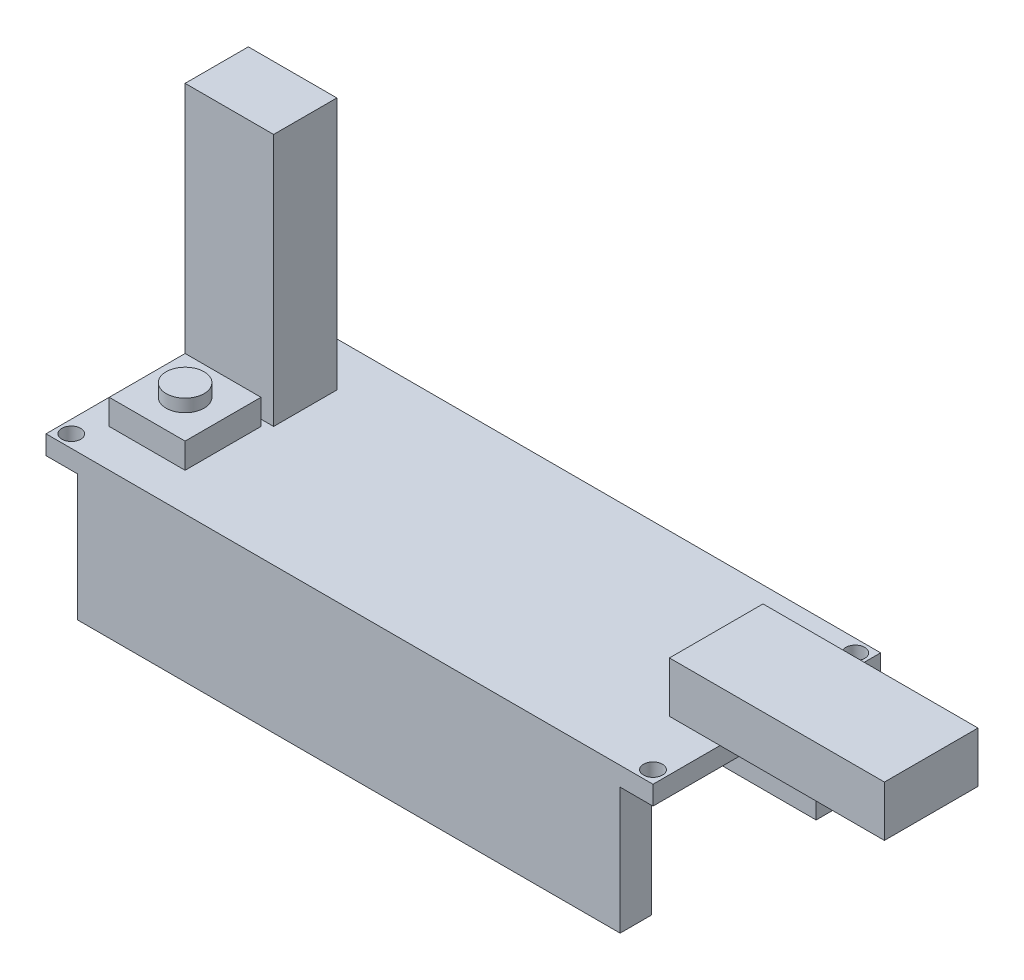
SolidWorks part; units mm, degrees
ref_plane "Спереди" through (0, 0, 0) normal (0, 0, 1) x (1, 0, 0)
ref_plane "Сверху" through (0, 0, 0) normal (0, 1, 0) x (1, 0, 0)
ref_plane "Справа" through (0, 0, 0) normal (1, 0, 0) x (0, 0, -1)
sketch "Эскиз1" plane through (0, 0, 0) normal (0, 1, 0) x (1, 0, 0)
  line L0 (0, 0) -> (-48, 0)
  line L1 (-48, 0) -> (-48, 18)
  line L2 (-48, 18) -> (0, 18)
  line L3 (0, 18) -> (0, 0)
extrude "Бобышка-Вытянуть1" add sketch "Эскиз1" along normal blind 1.5
sketch "Эскиз2" plane through (0, 1.5, 0) normal (0, 1, 0) x (1, 0, 0)
  line L0 (0, 9) -> (0, 12.7)
  line L1 (0, 0) -> (0, 18) construction
  line L2 (0, 12.7) -> (-4, 12.7)
  line L3 (-4, 12.7) -> (-4, 5.3)
  line L4 (-4, 5.3) -> (13, 5.3)
  line L5 (13, 5.3) -> (13, 12.7)
  line L6 (13, 12.7) -> (0, 12.7)
  line M1 (0, 0) -> (0, 18)
extrude "Бобышка-Вытянуть2" add sketch "Эскиз2" along normal blind 4 contours L5 L6 L4 M1 | L3 L4 L2 M1
sketch "Эскиз4" plane through (0, 0, 0) normal (0, -1, 0) x (-1, 0, 0)
  line L0 (0, 18) -> (2.6, 18)
  line L1 (0, 18) -> (48, 18) construction
  line L2 (48, 18) -> (45.5, 18)
  line L3 (45.5, 18) -> (2.6, 18)
  line L4 (2.6, 18) -> (2.6, 15.5)
  line L5 (2.6, 15.5) -> (45.5, 15.5)
  line L6 (45.5, 15.5) -> (45.5, 18)
  line L7 (0, 9) -> (48, 9) construction
  line L10 (45.5, 2.5) -> (45.5, 0)
  line L11 (2.6, 2.5) -> (45.5, 2.5)
  line L12 (2.6, 0) -> (2.6, 2.5)
  line L13 (45.5, 0) -> (2.6, 0)
  line L14 (48, 0) -> (45.5, 0)
  line L15 (0, 0) -> (2.6, 0)
  line M2 (0, 0) -> (48, 0)
  line M4 (48, 18) -> (0, 18)
extrude "Бобышка-Вытянуть3" add sketch "Эскиз4" along normal blind 10 contours L5 L6 L4 M4 | L12 L10 L11 M2
sketch "Эскиз5" plane through (0, 1.5, 0) normal (0, 1, 0) x (1, 0, 0)
  line L3 (-39.5, 18) -> (-39.5, 14.5)
  line L4 (0, 18) -> (-48, 18) construction
  line L5 (-39.5, 14.5) -> (-39.5, 9.5)
  line L6 (-39.5, 9.5) -> (-46.5, 9.5)
  line L7 (-46.5, 9.5) -> (-46.5, 14.5)
  line L8 (-46.5, 14.5) -> (-39.5, 14.5)
  dimension "D1" = 3.5
extrude "Бобышка-Вытянуть4" add sketch "Эскиз5" along normal blind 20 contours L8 L7 L6 L5
sketch "Эскиз6" plane through (0, 1.5, 0) normal (0, 1, 0) x (1, 0, 0)
  line L0 (-48, 0) -> (-46, 0)
  line L1 (-48, 0) -> (0, 0) construction
  line L2 (-46, 0) -> (-46, 3)
  line L3 (-46, 3) -> (-46, 9)
  line L4 (-46, 9) -> (-40, 9)
  line L5 (-40, 9) -> (-40, 3)
  line L6 (-40, 3) -> (-46, 3)
extrude "Бобышка-Вытянуть5" add sketch "Эскиз6" along normal blind 2 contours L6 L5 L4 L3
sketch "Эскиз7" plane through (0, 3.5, 0) normal (0, 1, 0) x (1, 0, 0)
  line L0 (-46, 9) -> (-40, 3)
  line L1 (-40, 3) -> (-40, 9)
  line L2 (-46, 9) -> (-40, 9) construction
  line L3 (-40, 9) -> (-46, 3)
  circle A0 centre (-43, 6) radius 1.5
extrude "Бобышка-Вытянуть6" add sketch "Эскиз7" along normal blind 1 contours L0 A0 L3
sketch "Эскиз8" plane through (0, 1.5, 0) normal (0, 1, 0) x (1, 0, 0)
  line L0 (0, 18) -> (-48, 18) construction
  line L2 (-48, 18) -> (-48, 0) construction
  line L3 (-48, 9) -> (-34.2096, 9) construction
  line L4 (-24, 18) -> (-24, -1.1436) construction
  circle A0 centre (-47, 17) radius 0.75
  circle A1 centre (-47, 1) radius 0.75
  circle A2 centre (-1, 1) radius 0.75
  circle A3 centre (-1, 17) radius 0.75
  dimension "D1" = 1
  dimension "D2" = 1
extrude "Вырез-Вытянуть1" cut sketch "Эскиз8" against normal blind 10
